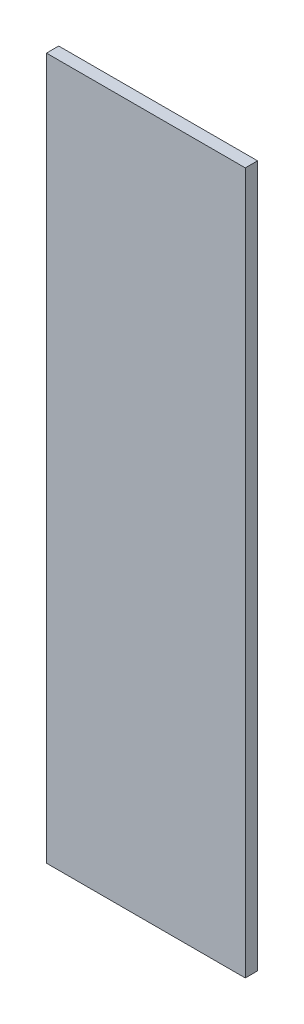
SolidWorks part; units mm, degrees
material "Дуб"
ref_plane "Спереди" through (0, 0, 0) normal (0, 0, 1) x (1, 0, 0)
ref_plane "Сверху" through (0, 0, 0) normal (0, 1, 0) x (1, 0, 0)
ref_plane "Справа" through (0, 0, 0) normal (1, 0, 0) x (0, 0, -1)
sketch "Эскиз1" plane through (0, 0, 0) normal (0, 0, 1) x (1, 0, 0)
  line L1 (-971.5789, 1061.8421) -> (-322.5789, 1061.8421)
  line L2 (-971.5789, 1061.8421) -> (-971.5789, -1228.1579)
  line L3 (-971.5789, -1228.1579) -> (-322.5789, -1228.1579)
  line L4 (-322.5789, 1061.8421) -> (-322.5789, -1228.1579)
  dimension "D1" = 649
  dimension "D2" = 2290
extrude "Бобышка-Вытянуть1" add sketch "Эскиз1" along normal blind 40
